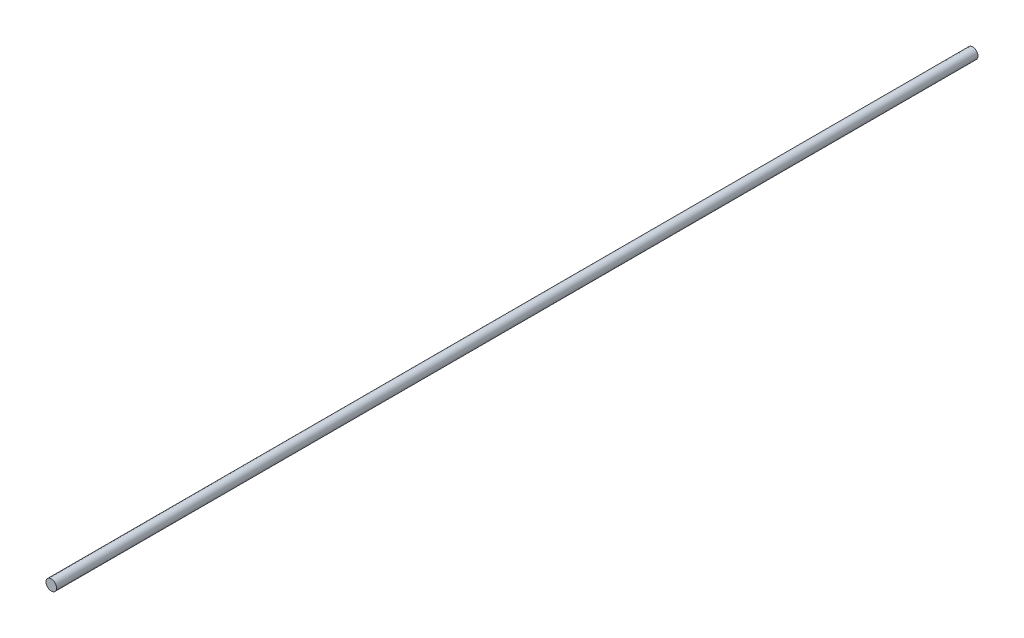
SolidWorks part; units mm, degrees
material "Aluminum"
ref_plane "Front Plane" through (0, 0, 0) normal (0, 0, 1) x (1, 0, 0)
ref_plane "Top Plane" through (0, 0, 0) normal (0, 1, 0) x (1, 0, 0)
ref_plane "Right Plane" through (0, 0, 0) normal (1, 0, 0) x (0, 0, -1)
sketch "Sketch1" plane through (0, 0, 0) normal (0, 0, 1) x (1, 0, 0)
  circle A0 centre (0, 0) radius 6.35
  dimension "D1" = 12.7
extrude "Boss-Extrude1" add sketch "Sketch1" along normal blind 1106.4277
equation "\"d\"= 0.5"
equation "\"E\"= 9860000"
equation "\"F\"= 400"
equation "\"def\"= 0.009"
equation "\"A\"= ( pi * \"d\" ^ 2 ) / 4"
equation "\"L\"= ( \"def\" * \"E\" * pi * \"d\" ^ 2 ) / ( 4 * \"F\" )"
equation "\"D1@Sketch1\"=\"d\""
equation "\"D1@Boss-Extrude1\"=\"L\""
